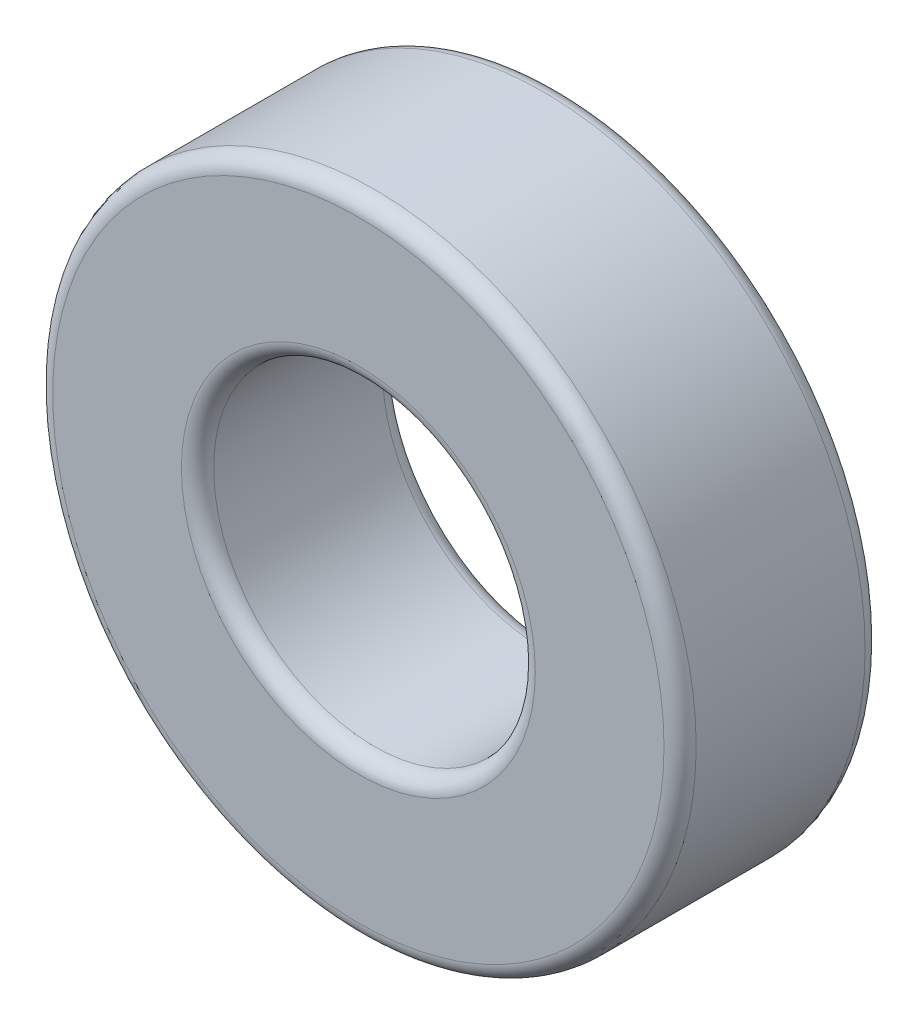
SolidWorks part; units mm, degrees
ref_plane "Front Plane" through (0, 0, 0) normal (0, 0, 1) x (1, 0, 0)
ref_plane "Top Plane" through (0, 0, 0) normal (0, 1, 0) x (1, 0, 0)
ref_plane "Right Plane" through (0, 0, 0) normal (1, 0, 0) x (0, 0, -1)
sketch "Sketch1" plane through (0, 0, 0) normal (0, 0, 1) x (1, 0, 0)
  circle A0 centre (60.3855, 2.9152) radius 4
  dimension "D1" = 8
extrude "Boss-Extrude1" add sketch "Sketch1" along normal blind 2.5
sketch "Sketch2" plane through (0, 0, 0) normal (0, 0, -1) x (-1, 0, 0)
  circle A0 centre (-60.3855, 2.9152) radius 2
  dimension "D1" = 4
extrude "Cut-Extrude1" cut sketch "Sketch2" against normal blind 4
fillet "Fillet1" radius 0.2 4 edges at (62.3855, 2.9152, 2.5) (64.3855, 2.9152, 2.5) (58.3855, 2.9152, 0) (64.3855, 2.9152, 0)
